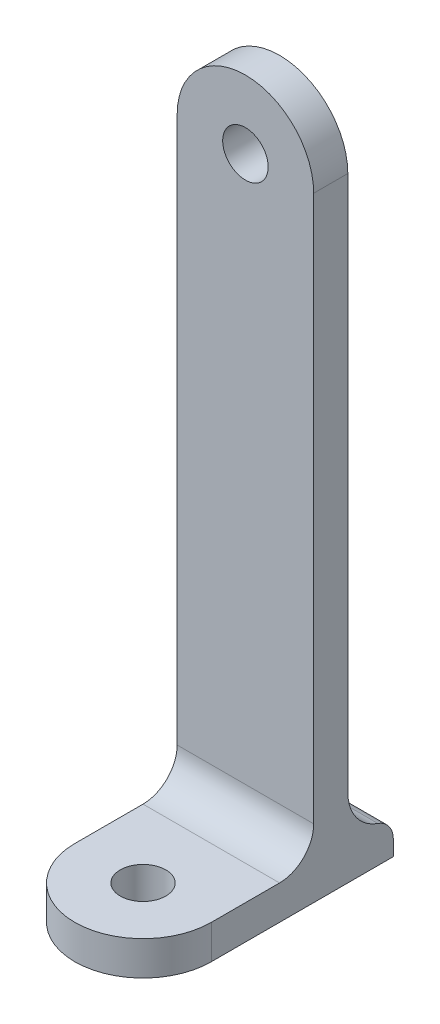
SolidWorks part; units mm, degrees
ref_plane "Front Plane" through (0, 0, 0) normal (0, 0, 1) x (1, 0, 0)
ref_plane "Top Plane" through (0, 0, 0) normal (0, 1, 0) x (1, 0, 0)
ref_plane "Right Plane" through (0, 0, 0) normal (1, 0, 0) x (0, 0, -1)
sketch "Sketch1" plane through (0, 0, 0) normal (0, 1, 0) x (1, 0, 0)
  line L0 (-6, 0) -> (-6, 16)
  line L1 (-6, 16) -> (6, 16)
  line L2 (6, 16) -> (6, 0)
  circle A0 centre (0, 0) radius 2
  circle A1 centre (0, 0) radius 6
  dimension "D1" = 4
  dimension "D2" = 4
  dimension "D3" = 16
extrude "Boss-Extrude1" add sketch "Sketch1" along normal blind 3 contours A1 L2 L1 L0 | A1 A0
sketch "Sketch2" plane through (6, 0, 0) normal (1, 0, 0) x (0, 0, -1)
  line L0 (12, 3) -> (12, 60)
  line L1 (16, 3) -> (0, 3) construction
  line L2 (12, 60) -> (9, 60)
  line L3 (9, 60) -> (9, 3)
  line L8 (0, 0) -> (16, 0)
  line L9 (16, 0) -> (16, 3)
  line L10 (16, 3) -> (0, 3)
  line L11 (0, 3) -> (0, 0)
  line L14 (12, 3) -> (9, 3)
  dimension "D1" = 57
  dimension "D2" = 3
  dimension "D3" = 4
  dimension "D4" = 0
extrude "Boss-Extrude2" add sketch "Sketch2" against normal blind 12
sketch "Sketch3" plane through (0, 0, -9) normal (0, 0, 1) x (1, 0, 0)
  line L0 (-6, 60) -> (6, 60) construction
  line L1 (-6, 54) -> (-6, 60)
  line L2 (-6, 60) -> (6, 60)
  line L3 (6, 60) -> (6, 54)
  circle A0 centre (0, 54) radius 2
  circle A1 centre (0, 54) radius 6
  line M3 (6, 3) -> (6, 60)
  line M4 (6, 60) -> (-6, 60)
  line M5 (-6, 60) -> (-6, 3)
  dimension "D1" = 4
  dimension "D2" = 4
extrude "Cut-Extrude1" cut sketch "Sketch3" against normal up to next contours A1 L2 M5 | A1 M3 M4 | A0
fillet "Fillet1" radius 3 1 edges at (0, 3, -9)
fillet "Fillet2" radius 3.9 1 edges at (0, 3, -12)
fillet "Fillet3" radius 2 1 edges at (0, 3, -16)
